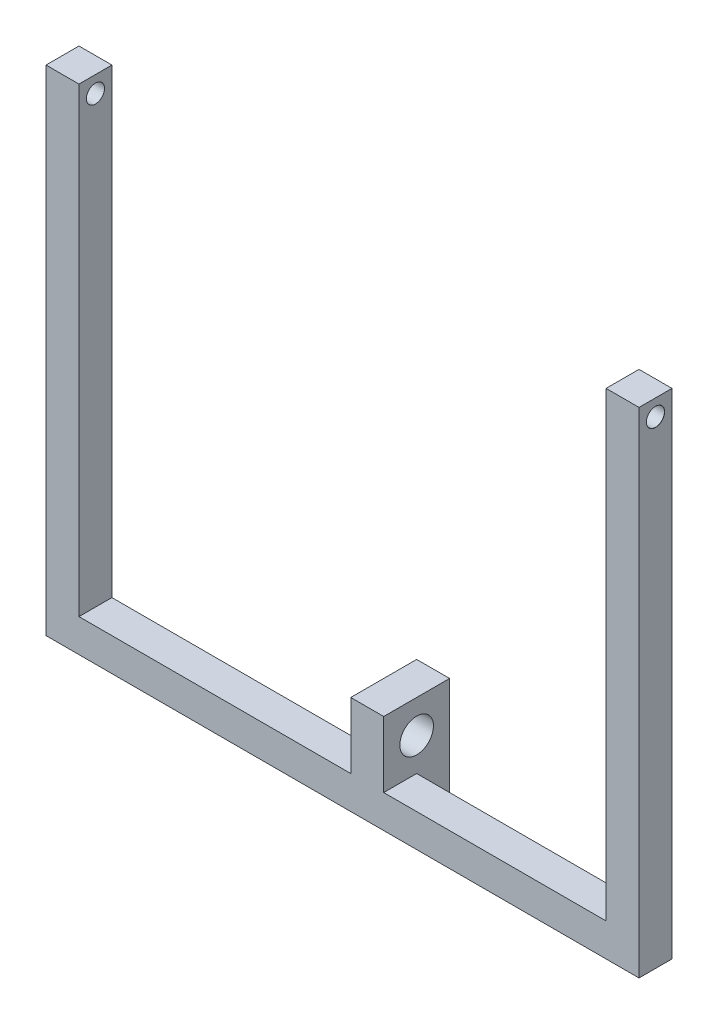
SolidWorks part; units mm, degrees
ref_plane "Front Plane" through (0, 0, 0) normal (0, 0, 1) x (1, 0, 0)
ref_plane "Top Plane" through (0, 0, 0) normal (0, 1, 0) x (1, 0, 0)
ref_plane "Right Plane" through (0, 0, 0) normal (1, 0, 0) x (0, 0, -1)
sketch "Sketch1" plane through (0, 0, 0) normal (0, 1, 0) x (1, 0, 0)
  line L1 (-90, 5) -> (90, 5)
  line L2 (-90, 5) -> (-90, -5)
  line L3 (-90, -5) -> (90, -5)
  line L4 (90, 5) -> (90, -5)
  line L5 (-90, 5) -> (90, -5) construction
  line L6 (-90, -5) -> (90, 5) construction
  point P0 (0, 0)
  dimension "D1" = 180
  dimension "D2" = 10
extrude "Boss-Extrude1" add sketch "Sketch1" along normal blind 10
sketch "Sketch2" plane through (0, 10, 0) normal (0, 1, 0) x (1, 0, 0)
  line L0 (-90, -5) -> (90, -5) construction
  line L1 (-90, 5) -> (-80, 5)
  line L2 (-90, 5) -> (-90, -5)
  line L3 (-90, -5) -> (-80, -5)
  line L4 (-80, 5) -> (-80, -5)
  line L6 (90, 5) -> (80, 5)
  line L7 (90, 5) -> (90, -5)
  line L8 (90, -5) -> (80, -5)
  line L9 (80, 5) -> (80, -5)
  dimension "D1" = 10
extrude "Boss-Extrude2" add sketch "Sketch2" along normal blind 140
sketch "Sketch5" plane through (90, 0, 0) normal (1, 0, 0) x (0, 0, -1)
  line L0 (-5, 150) -> (5, 150) construction
  point P0 (0, 145)
  point P5 (0, 150)
  dimension "D1" = 5
hole_wizard "M5 Clearance Hole1" positions "Sketch5" profile "Sketch4" hole size "M5" standard "ANSI Metric" end condition through all
sketch "Sketch4" plane through (90, 145, 0) normal (0, 1, 0) x (0, 0, -1)
  line L0 (0, 0) -> (0, 180)
  line L1 (0, 180) -> (2.75, 180)
  line L2 (2.75, 180) -> (2.75, 0.025)
  line L3 (2.75, 0.025) -> (2.775, 0)
  line L5 (2.775, 0) -> (0, 0)
  line L6 (-2.75, 0.025) -> (-2.775, 0) construction
  line L11 (0, -6.35) -> (0, 107.95) construction
  dimension "Thru Hole Dia." = 5.5
  dimension "Thru Hole Depth" = 180
  dimension "Near C'Sink Dia." = 5.55
  dimension "Near C'Sink Angle" = 90
sketch "Sketch6" plane through (0, 0, 0) normal (1, 0, 0) x (0, 0, -1)
  line L0 (5, 0) -> (5, 10)
  line L1 (5, 0) -> (15, 0)
  line L3 (-5, 30) -> (15, 30)
  line L4 (15, 0) -> (15, 30)
  line L5 (5, 10) -> (-5, 10)
  line L7 (-5, 0) -> (5, 0) construction
  line L8 (-5, 10) -> (-5, 30)
  line L9 (-5, 150) -> (-5, 0) construction
  point P0 (-6.0088, 32.6125)
  dimension "D1" = 20
  dimension "D2" = 30
extrude "Boss-Extrude3" add sketch "Sketch6" along normal blind 10 from offset 2.5
sketch "Sketch9" plane through (2.5, 0, 0) normal (-1, 0, 0) x (0, 0, 1)
  line L2 (-15, 30) -> (5, 30) construction
  line L3 (5, 150) -> (5, 0) construction
  point P0 (-5, 20)
  dimension "D1" = 10
  dimension "D2" = 10
hole_wizard "Hole1" positions "Sketch9" profile "Sketch8" legacy
sketch "Sketch8" plane through (2.5, 20, -5) normal (0, 1, 0) x (0, 0, 1)
  line L0 (0, 0) -> (0, 10)
  line L1 (0, 10) -> (5.1, 10)
  line L2 (5.1, 10) -> (5.1, 0.6)
  line L3 (5.1, 0.6) -> (5.7, 0.6)
  line L4 (5.7, 0.6) -> (5.7, 0)
  line L5 (5.7, 0) -> (0, 0)
  line L6 (0, 110) -> (0, -10) construction
  dimension "Diameter" = 10.2
  dimension "Depth" = 10
  dimension "C-Bore Diameter" = 11.4
  dimension "C-Bore Depth" = 0.6
